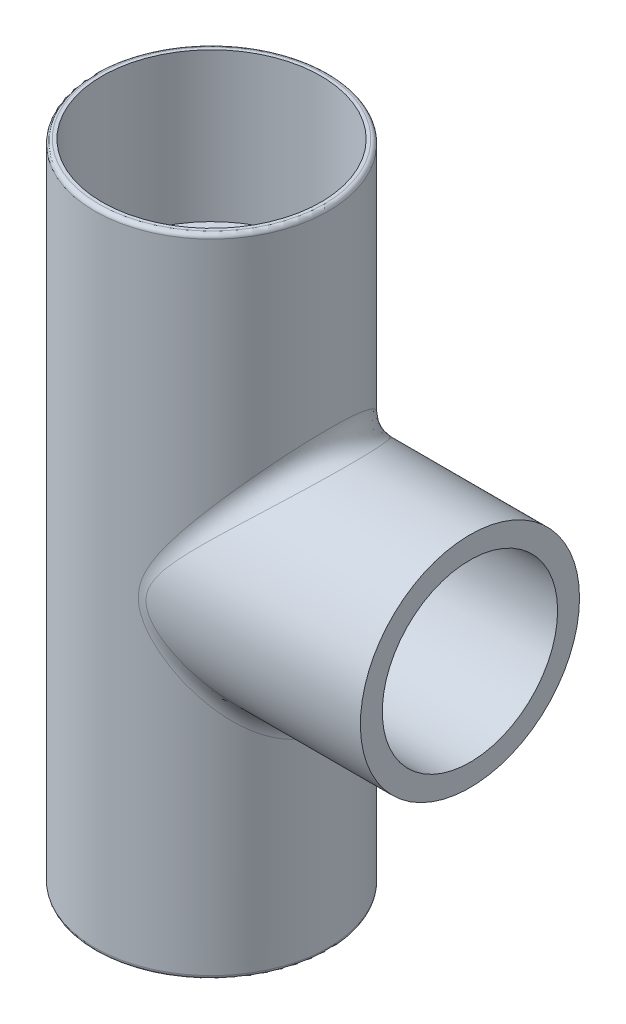
SolidWorks part; units mm, degrees
ref_plane "Front Plane" through (0, 0, 0) normal (0, 0, 1) x (1, 0, 0)
ref_plane "Top Plane" through (0, 0, 0) normal (0, 1, 0) x (1, 0, 0)
ref_plane "Right Plane" through (0, 0, 0) normal (1, 0, 0) x (0, 0, -1)
sketch "Sketch1" plane through (0, 0, 0) normal (0, 1, 0) x (1, 0, 0)
  circle A0 centre (0, 0) radius 0.565
  dimension "D1" = 1.13
extrude "Boss-Extrude1" add sketch "Sketch1" along normal blind 3.125
ref_plane "Plane1" through (0, 1.5625, 0) normal (0, -1, 0) x (-1, 0, 0)
sketch "Sketch2" plane through (0, 1.5625, 0) normal (0, -1, 0) x (-1, 0, 0)
  circle A0 centre (0, 0) radius 0.412
  dimension "D1" = 0.824
sketch "Sketch3" plane through (0, 0, 0) normal (0, -1, 0) x (1, 0, 0)
  circle A0 centre (0, 0) radius 0.529
  dimension "D1" = 1.058
extrude "Cut-Extrude2" cut sketch "Sketch3" against normal blind 0.72
sketch "Sketch4" plane through (0, 3.125, 0) normal (0, 1, 0) x (1, 0, 0)
  circle A0 centre (0, 0) radius 0.529
  dimension "D1" = 1.058
extrude "Cut-Extrude3" cut sketch "Sketch4" against normal blind 0.72
sketch "Sketch5" plane through (0, 0, 0) normal (1, 0, 0) x (0, 0, -1)
  line L0 (-0.565, 3.125) -> (0.565, 0) construction
  line L1 (0.565, 3.125) -> (-0.565, 0) construction
  circle A0 centre (0, 1.5625) radius 0.53
  dimension "D1" = 1.06
extrude "Boss-Extrude2" add sketch "Sketch5" along normal blind 1.25
sketch "Sketch6" plane through (0, 0, 0) normal (1, 0, 0) x (0, 0, -1)
  line L0 (-0.412, 1.5625) -> (0.412, 1.5625) construction
  circle A0 centre (0, 1.5625) radius 0.311
  dimension "D1" = 0.622
extrude "Cut-Extrude8" cut sketch "Sketch6" along normal blind 1.25
sketch "Sketch9" plane through (1.25, 0, 0) normal (1, 0, 0) x (0, 0, -1)
  line L0 (-0.412, 1.5625) -> (0.412, 1.5625) construction
  circle A0 centre (0, 1.5625) radius 0.424
  dimension "D1" = 0.848
extrude "Cut-Extrude10" cut sketch "Sketch9" against normal blind 0.69
sketch "Sketch10" plane through (0, 2.405, 0) normal (0, 1, 0) x (1, 0, 0)
  circle A0 centre (0, 0) radius 0.412
  dimension "D1" = 0.824
extrude "Cut-Extrude12" cut sketch "Sketch10" against normal mid plane 8.125
fillet "Fillet1" radius 0.02 2 edges at (0, 0, 0.565) (0, 3.125, 0.565)
fillet "Fillet2" radius 0.1 1 edges at (0.2021, 1.6128, -0.5276)
